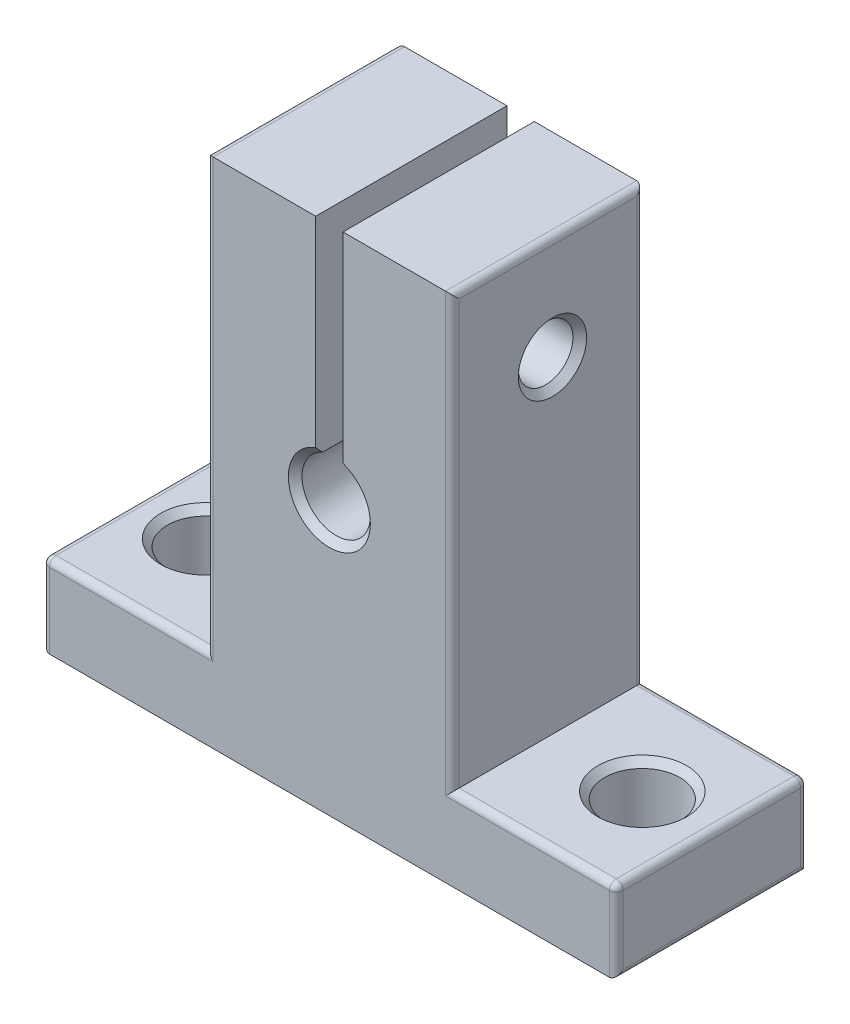
SolidWorks part; units mm, degrees
material "1060 Alloy"
ref_plane "Front Plane" through (0, 0, 0) normal (0, 0, 1) x (1, 0, 0)
ref_plane "Top Plane" through (0, 0, 0) normal (0, 1, 0) x (1, 0, 0)
ref_plane "Right Plane" through (0, 0, 0) normal (1, 0, 0) x (0, 0, -1)
sketch "Sketch1" plane through (0, 0, 0) normal (0, 0, 1) x (1, 0, 0)
  line L0 (0, 0) -> (-50000, 0) construction
  line L1 (0, 0) -> (0, 50000) construction
  line L2 (-21, -3) -> (-21, 3)
  line L3 (-21, 3) -> (-9, 3)
  line L4 (-9, 3) -> (-9, 34.5)
  line L5 (-9, 34.5) -> (-1, 34.5)
  line L6 (9, 34.5) -> (9, 3)
  line L7 (9, 3) -> (21, 3)
  line L8 (21, 3) -> (21, -3)
  line L9 (21, -3) -> (-21, -3)
  line L10 (16, -3) -> (16, 3) construction
  line L11 (-16, -3) -> (-16, 3) construction
  line L12 (-1, 34.5) -> (-1, 19.2913)
  line L13 (1, 34.5) -> (1, 19.2913)
  line L14 (1, 34.5) -> (9, 34.5)
  arc A0 (-1, 19.2913) -> (1, 19.2913) centre (0, 17) ccw
  point P8 (-21, 0)
  point P15 (0, -3)
  point P21 (16, 0)
  dimension "Shaft Diameter" = 5
  dimension "W" = 42
  dimension "P" = 18
  dimension "F" = 37.5
  dimension "G" = 6
  dimension "B" = 32
  dimension "D1" = 2
  dimension "h" = 20
extrude "Boss-Extrude1" add sketch "Sketch1" along normal mid plane 14
sketch "Sketch2" plane through (0, 3, 0) normal (0, 1, 0) x (1, 0, 0)
  line L0 (0, 0) -> (50000, 0) construction
  line L1 (0.3141, 0) -> (-49999.6859, 0) construction
  line L2 (-0.0955, 2.4842) -> (-0.0955, 50002.4842) construction
  circle A0 centre (15.9045, 0) radius 2.75
  circle A1 centre (-16.0955, 0) radius 2.75
  dimension "B" = 32
  dimension "S" = 5.5
extrude "Cut-Extrude1" cut sketch "Sketch2" against normal through all
sketch "Sketch5" plane through (-1, 0, 0) normal (1, 0, 0) x (0, 0, -1)
  line L0 (-7, 26.8956) -> (7, 26.8956) construction
  line L1 (7, 19.2913) -> (7, 34.5) construction
  line L2 (0, 34.5) -> (0, 19.2913) construction
  line L3 (-7, 34.5) -> (7, 34.5) construction
  line L4 (-7, 19.2913) -> (7, 19.2913) construction
  line L5 (-7, 19.2913) -> (-7, 34.5) construction
  circle A0 centre (0.3307, 26.8956) radius 2
  dimension "Clamping bold" = 4
extrude "Cut-Extrude2" cut sketch "Sketch5" against normal through all both and the other way through all
chamfer "Chamfer2" distance 0.5 angle 45 6 edges at (0, 14.5, -7) (0, 14.5, 7) (-9, 26.8956, -2.3307) (-13.3455, 3, 0) (9, 26.8956, 1.6693) (13.1545, 3, 0)
fillet "Fillet2" radius 0.5 18 edges at (21, -3, 0) (21, 0, 7) (21, 3, 0) (21, 0, -7) (-21, 3, 0) (-21, 0, 7) (-21, -3, 0) (-21, 0, -7) (-15, 3, -7) (-15, 3, 7) (-9, 18.75, 7) (-9, 34.5, 0) (-9, 18.75, -7) (9, 18.75, -7) (9, 18.75, 7) (15, 3, 7) (15, 3, -7) (9, 34.5, 0)
equation "\"W\"= \"W@Sketch1\"'Width"
equation "\"B\"= \"B@Sketch1\"'between hold"
equation "\"F\"= \"F@Sketch1\"'Hight"
equation "\"P\"= \"P@Sketch1\""
equation "\"G\"= \"G@Sketch1\""
equation "\"Shaft diameter\"= \"Shaft Diameter@Sketch1\""
equation "\"S\"= 5.5'M5"
equation "\"Clamping bold\"= 4'M4"
equation "\"h\"= \"h@Sketch1\""
